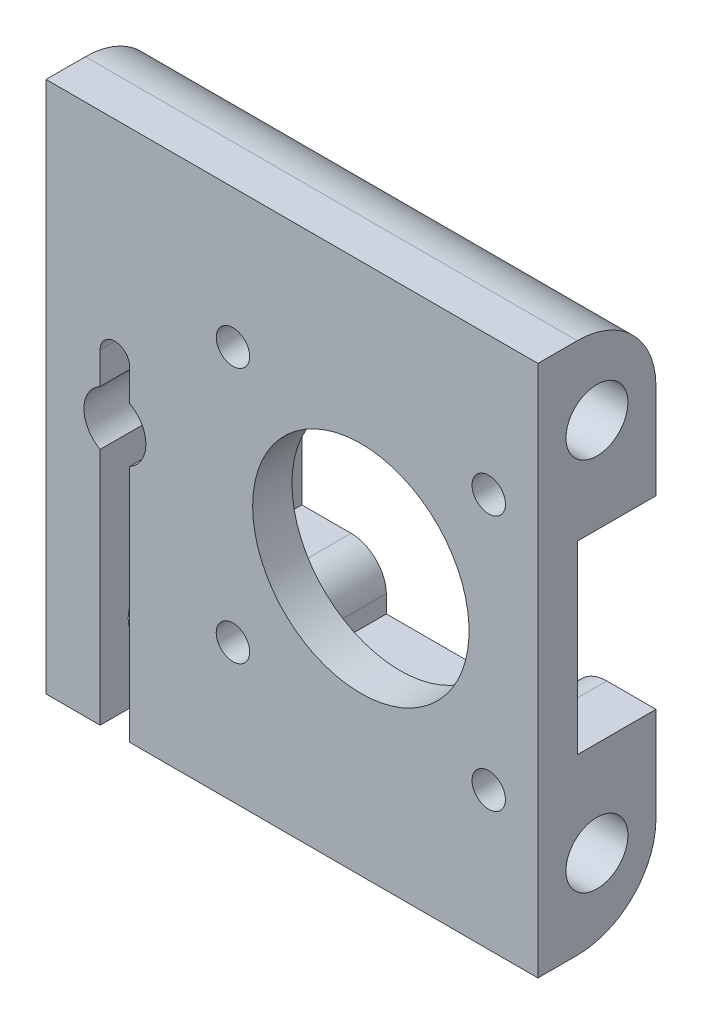
SolidWorks part; units mm, degrees
ref_plane "Front Plane" through (0, 0, 0) normal (0, 0, 1) x (1, 0, 0)
ref_plane "Top Plane" through (0, 0, 0) normal (0, 1, 0) x (1, 0, 0)
ref_plane "Right Plane" through (0, 0, 0) normal (1, 0, 0) x (0, 0, -1)
sketch "Sketch1" plane through (0, 0, 0) normal (0, 0, 1) x (1, 0, 0)
  line L1 (0, 0) -> (50, 0)
  line L2 (0, 0) -> (0, 54.105)
  line L3 (0, 54.105) -> (50, 54.105)
  line L4 (50, 0) -> (50, 54.105)
  dimension "D1" = 54.105
  dimension "D2" = 50
extrude "Boss-Extrude1" add sketch "Sketch1" along normal blind 12
sketch "Sketch2" plane through (0, 0, 0) normal (1, 0, 0) x (0, 0, -1)
  line L0 (-12, 27.0525) -> (0, 27.0525) construction
  line L1 (-12, 0) -> (-12, 54.105) construction
  line L2 (0, 0) -> (0, 54.105) construction
  circle A0 centre (-6, 46.105) radius 3.15
  circle A1 centre (-6, 8) radius 3.15
  dimension "D2" = 6.3
  dimension "D1" = 6
  dimension "D3" = 19.0525
extrude "Cut-Extrude1" cut sketch "Sketch2" along normal through all
fillet "Fillet1" radius 8 2 edges at (25, 0, 0) (25, 54.105, 0)
sketch "Sketch3" plane through (0, 0, 0) normal (0, 0, -1) x (-1, 0, 0)
  line L0 (-50, 27.0525) -> (0, 27.0525) construction
  line L1 (-50, 8) -> (-50, 46.105) construction
  line L2 (0, 46.105) -> (0, 8) construction
  line L3 (-8.5, 0) -> (-8.5, 24.2826)
  line L5 (-5.5, 33.0525) -> (-5.5, 29.8224)
  line L6 (0, 0) -> (-50, 0) construction
  line L7 (-8.5, 0) -> (-5.5, 0)
  line L8 (-8.5, 29.8224) -> (-8.5, 33.0525)
  line L9 (-5.5, 24.2826) -> (-5.5, 0)
  arc A0 (-8.5, 29.8224) -> (-8.5, 24.2826) centre (-7, 27.0525) ccw
  circle A1 centre (-32, 27.0525) radius 11
  circle A2 centre (-19, 40.0525) radius 1.7
  circle A3 centre (-19, 14.0525) radius 1.7
  arc A4 (-5.5, 24.2826) -> (-5.5, 29.8224) centre (-7, 27.0525) ccw
  arc A5 (-5.5, 33.0525) -> (-8.5, 33.0525) centre (-7, 33.0525) ccw
  circle A6 centre (-45, 14.0525) radius 1.7
  circle A7 centre (-45, 40.0525) radius 1.7
  dimension "D1" = 22
  dimension "D2" = 6.3
  dimension "D5" = 3.4
  dimension "D6" = 1.5
  dimension "D7" = 13
  dimension "D10" = 13
  dimension "D3" = 7
  dimension "D4" = 25
  dimension "D8" = 3
  dimension "D9" = 6
  dimension "D11" = 4
extrude "Cut-Extrude2" cut sketch "Sketch3" against normal through all
sketch "Sketch5" plane through (0, 0, 0) normal (0, 0, -1) x (-1, 0, 0)
  line L0 (-50, 27.0525) -> (-29.1332, 27.0525) construction
  line L1 (-19, 17.6525) -> (-14, 17.6525)
  line L2 (-50, 36.4525) -> (-50, 17.6525)
  line L4 (-14, 36.4525) -> (-14, 17.6525)
  line L5 (-50, 8) -> (-50, 46.105) construction
  line L7 (0, 46.105) -> (0, 8) construction
  line L8 (-41.4013, 41.7525) -> (-22.5987, 41.7525)
  line L9 (-22.5987, 41.7525) -> (-22.5987, 39.955)
  line L10 (-41.4013, 39.955) -> (-41.4013, 41.7525)
  line L11 (-45, 36.4525) -> (-50, 36.4525)
  line L12 (-19, 36.4525) -> (-14, 36.4525)
  line L13 (-45, 17.6525) -> (-50, 17.6525)
  line L14 (-41.4013, 14.15) -> (-41.4013, 12.3525)
  line L15 (-22.5987, 12.3525) -> (-22.5987, 14.15)
  line L16 (-41.4013, 12.3525) -> (-22.5987, 12.3525)
  arc A0 (-45, 36.4525) -> (-41.4013, 39.955) centre (-45, 40.0525) ccw
  arc A1 (-22.5987, 39.955) -> (-19, 36.4525) centre (-19, 40.0525) ccw
  circle A2 centre (-45, 40.0525) radius 1.7 construction
  circle A3 centre (-19, 40.0525) radius 1.7 construction
  arc A4 (-22.5987, 14.15) -> (-19, 17.6525) centre (-19, 14.0525) cw
  arc A5 (-45, 17.6525) -> (-41.4013, 14.15) centre (-45, 14.0525) cw
  dimension "D5" = 3.6
  dimension "D4" = 14
extrude "Cut-Extrude4" cut sketch "Sketch5" against normal offset from surface (8 mm away) 4 up to face at (43.3, 40.0525, 12)
sketch "Sketch4" plane through (0, 0, 0) normal (0, 0, -1) x (-1, 0, 0)
  circle A0 centre (-32, 27.0525) radius 6.7
  circle A1 centre (-32, 27.0525) radius 11 construction
  dimension "D1" = 13.4
extrude "Cut-Extrude3" [suppressed] cut sketch "Sketch4" against normal offset from surface (9 mm away) 3
